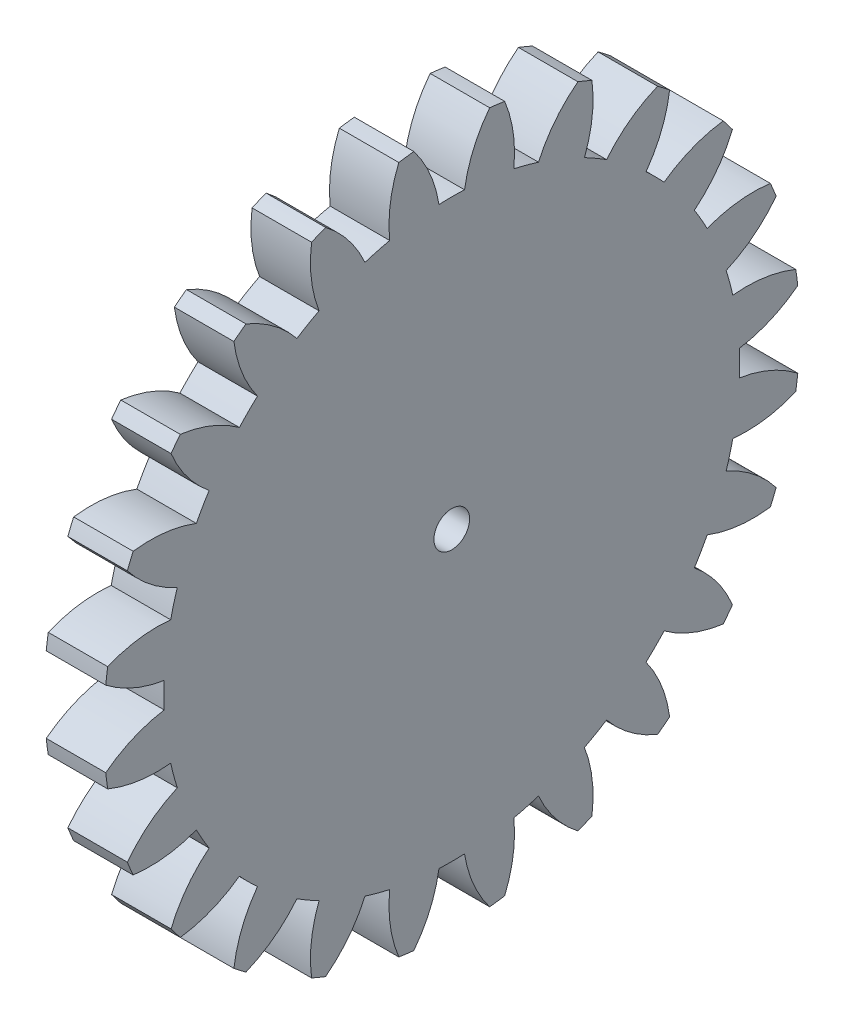
SolidWorks part; units mm, degrees
ref_plane "Plane1" through (0, 0, 0) normal (0, 0, 1) x (1, 0, 0)
ref_plane "Plane2" through (0, 0, 0) normal (0, 1, 0) x (1, 0, 0)
ref_plane "Plane3" through (0, 0, 0) normal (1, 0, 0) x (0, 0, -1)
other "Configuration Table"
sketch "HoldingSke" plane through (0, 0, 0) normal (0, 1, 0) x (1, 0, 0)
  line L0 (0, 0) -> (0.406, -0.1808)
  line L1 (-15, 0) -> (100, 0) construction
  line L2 (0, 0) -> (-2.1039, 2.3779)
  line L3 (0, 0) -> (-11.863, 4.5341)
  line L4 (0, 0) -> (7.8894, 3.5126)
  line L5 (0, 0) -> (-46.8476, -17.4728)
  line L6 (0, 0) -> (-4.1448, -2.7965)
  line L7 (-2.1039, 2.3779) -> (8.6586, 51.2059)
  line L8 (-76.2, 54.61) -> (-75.7, 54.61)
  line L9 (-71.009, 38.7566) -> (-53.1078, 45.2721)
  line L10 (-76.2, 71.12) -> (104.1128, 71.12)
  line L11 (0, 0) -> (-5, 0)
  line L12 (-76.2, 101.6) -> (-76.123, 101.6)
  line L13 (24.9733, 27.94) -> (52.9518, 28.4284)
  line L14 (24.9733, 27.94) -> (24.9743, 27.94)
  line L15 (24.9733, 27.94) -> (100.4006, 29.5858)
  line L16 (-63.627, -2.25) -> (-12.827, -2.25)
  circle A0 centre (0, 0) radius 1.5
  circle A1 centre (0, 0) radius 24.1865
  circle A2 centre (0, 0) radius 37.5
  circle A3 centre (0, 0) radius 1.5
  dimension "MHD" = 48.373
  dimension "Hub_dia" = 75
  dimension "Bore" = 3
  dimension "MBD" = 3
  dimension "Num_teeth" = 24
  dimension "Pitch" = 0.4444
  dimension "Overall_len" = 50
  dimension "Show_teeth" = 24
  dimension "Thickness" = 5
  dimension "OAL" = 50.0001
  dimension "T_dim" = 0.5
  dimension "Ap" = 20
  dimension "H" = 19.05
  dimension "Pitch_radius" = 180.3128
  dimension "Width" = 5
  dimension "Backlash" = 0.077
  dimension "Addendum_fac" = 1
  dimension "Dedendum_fac" = 1.25
  dimension "Clearance_fac" = 0.25
  dimension "Dedendum_add" = 0.001
  dimension "Module" = 2.25
sketch "BasProSke" plane through (0, 0, 0) normal (0, 1, 0) x (1, 0, 0)
  line L0 (-10, 0) -> (60, 0) construction
  line L1 (0, 0) -> (0, 29.25)
  line L2 (0, 0) -> (5, 0)
  line L3 (5, 0) -> (5, 29.25)
  line L4 (5, 29.25) -> (0, 29.25)
  dimension "Thickness" = 5
  dimension "Diameter" = 58.5
revolve "Base-Revolve" add sketch "BasProSke" angle 360 about L0
sketch "TooCutSke" plane through (0, 0, 0) normal (1, 0, 0) x (0, 0, -1)
  line L1 (0, 0) -> (0, 107) construction
  line L2 (0, 0) -> (-1.9006, 26.933) construction
  line L3 (0, 0) -> (-7.0355, 53.4402) construction
  line L4 (-1.9006, 26.933) -> (-3.5178, 26.7201) construction
  arc A0 (1.0746, 24.1626) -> (-1.0746, 24.1626) centre (0, 0) ccw
  arc A1 (3.2031, 29.0996) -> (-3.2031, 29.0996) centre (0, 0) ccw
  circle A2 centre (0, 0) radius 27 construction
  circle A3 centre (0, 0) radius 25.3717 construction
  arc A4 (-1.0746, 24.1626) -> (-3.2031, 29.0996) centre (-11.7443, 22.4899) ccw
  arc A5 (3.2031, 29.0996) -> (1.0746, 24.1626) centre (11.7443, 22.4899) ccw
  dimension "Root_dia" = 48.373
  dimension "Overcut_dia" = 58.5508
  dimension "Pitch_dia" = 54
  dimension "Base_dia" = 50.7434
  dimension "Flank_rad" = 10.8
  dimension "Half_ang" = 7.5
  dimension "Half_CT" = 1.6311
extrude "ToothCut" cut sketch "TooCutSke" along normal through all
fillet "Breaks" [suppressed] radius 0.045
fillet "RootFillets" [suppressed] radius 0.5635
pattern_circular "TeethCuts" count 24 every 15 about axis through (-10, 0, 0) along (1, 0, 0) of "ToothCut", "RootFillets", "Breaks"
sketch "HubNeaOneSke" plane through (0, 0, 0) normal (-1, 0, 0) x (0, 0, 1)
  circle A0 centre (0, 0) radius 24.1865
  dimension "Diameter" = 48.373
extrude "HubNearOne" [suppressed] add sketch "HubNeaOneSke" along normal blind 45.0001
sketch "HubNeaBotSke" plane through (0, 0, 0) normal (-1, 0, 0) x (0, 0, 1)
  circle A0 centre (0, 0) radius 24.1865
  dimension "Diameter" = 48.373
extrude "HubNearBoth" [suppressed] add sketch "HubNeaBotSke" along normal blind 22.5
ref_plane "FarPln" through (5, 0, 0) normal (1, 0, 0) x (0, 0, -1)
sketch "HubFarSke" plane through (5, 0, 0) normal (1, 0, 0) x (0, 0, -1)
  circle A0 centre (0, 0) radius 24.1865
  dimension "Diameter" = 48.373
extrude "HubFar" [suppressed] add sketch "HubFarSke" along normal blind 22.5
sketch "BorSke" plane through (0, 0, 0) normal (1, 0, 0) x (0, 0, -1)
  circle A0 centre (0, 0) radius 1.5
  dimension "Diameter" = 3
extrude "Bore" cut sketch "BorSke" along normal mid plane 100.0001
sketch "KeySke" plane through (0, 0, 0) normal (1, 0, 0) x (0, 0, -1)
  line L0 (-0.6, 0) -> (-0.6, 2)
  line L1 (-0.6, 2) -> (0.6, 2)
  line L2 (0.6, 2) -> (0.6, 0)
  line L3 (0, 0) -> (0, 34) construction
  line L4 (-0.6, 0) -> (0.6, 0)
  dimension "Offset" = 2
  dimension "Width" = 1.2
extrude "Keyway" [suppressed] cut sketch "KeySke" along normal mid plane 100.0001
pattern_circular "Keyway2" [suppressed] count 2 every 90 about axis through (-10, 0, 0) along (1, 0, 0)
equation "' \"Module@HoldingSke\" = 6.35"
equation "' \"Num_teeth@HoldingSke\" = 12"
equation "' \"Ap@HoldingSke\" =  20"
equation "' \"Ap@HoldingSke\" = 20"
equation "' \"Width@HoldingSke\" = 0.5 * 25.4"
equation "' \"Hub_dia@HoldingSke\"= 1 * 25.4"
equation "' \"Hub_dia@HoldingSke\" = 1 * 25.4"
equation "' \"Overall_len@HoldingSke\" = 1.0 * 25.4"
equation "' \"Bore@HoldingSke\" = 0.75 * 25.4"
equation "' \"T_dim@HoldingSke\" = 0.1 * 25.4"
equation "' \"Width@KeySke\" = 0.25 * 25.4"
equation "' \"Show_teeth@HoldingSke\" = 13"
equation "' \"Backlash@HoldingSke\" = 0.009 * 25.4"
equation "' \"Addendum_fac@HoldingSke\" = 1.0"
equation "' \"Dedendum_fac@HoldingSke\" = 1.25"
equation "' \"Dedendum_add@HoldingSke\" = 0.00005 * 25.4"
equation "' \"Clearance_fac@HoldingSke\" = 0.25"
equation "\"Pitch@HoldingSke\" = 1 / \"Module@HoldingSke\""
equation "\"Overcut_dia@TooCutSke\" = (\"Num_teeth@HoldingSke\" + 2 * \"Addendum_fac@HoldingSke\") / \"Pitch@HoldingSke\" + 0.002 * 25.4"
equation "\"Pitch_dia@TooCutSke\" = \"Num_teeth@HoldingSke\" / \"Pitch@HoldingSke\""
equation "\"Base_dia@TooCutSke\" = \"Num_teeth@HoldingSke\" / \"Pitch@HoldingSke\" * cos((\"Ap@HoldingSke\"  * 3.14159265 / 180))"
equation "\"Root_dia@TooCutSke\" = (\"Num_teeth@HoldingSke\" + 2) / \"Pitch@HoldingSke\" - 2 * (\"Addendum_fac@HoldingSke\" + \"Dedendum_fac@HoldingSke\") / \"Pitch@HoldingSke\" - \"Dedendum_add@HoldingSke\" * 2"
equation "\"Half_ang@TooCutSke\" = 180 / \"Num_teeth@HoldingSke\""
equation "\"Half_CT@TooCutSke\" = \"Num_teeth@HoldingSke\" / \"Pitch@HoldingSke\" * sin((3.14159265 / 2 / \"Num_teeth@HoldingSke\")) / 2 - 7 * \"Backlash@HoldingSke\" / 4"
equation "\"Flank_rad@TooCutSke\" = \"Num_teeth@HoldingSke\" / \"Pitch@HoldingSke\" / 5"
equation "\"Radius@RootFillets\" = \"Clearance_fac@HoldingSke\" / \"Pitch@HoldingSke\" + \"Dedendum_add@HoldingSke\""
equation "\"Break_rad@Breaks\" = 0.02 / \"Pitch@HoldingSke\""
equation "\"Thickness@HoldingSke\" = \"Width@HoldingSke\""
equation "\"OAL@HoldingSke\" = \"Thickness@HoldingSke\""
equation "\"MHD@HoldingSke\" = (\"Num_teeth@HoldingSke\" + 2) / \"Pitch@HoldingSke\" - 2 * (\"Addendum_fac@HoldingSke\" + \"Dedendum_fac@HoldingSke\")  / \"Pitch@HoldingSke\" - \"Dedendum_add@HoldingSke\" * 2"
equation "\"MBD@HoldingSke\" = (\"Num_teeth@HoldingSke\" + 2) / \"Pitch@HoldingSke\" - 2 * (\"Addendum_fac@HoldingSke\" + \"Dedendum_fac@HoldingSke\")  / \"Pitch@HoldingSke\" - \"Dedendum_add@HoldingSke\" * 2 - 0.002 * 25.4"
equation "\"MHD@HoldingSke\" = ((sgn( \"MHD@HoldingSke\" - \"Hub_dia@HoldingSke\" )-1)*( \"MHD@HoldingSke\" - \"Hub_dia@HoldingSke\" ))/-2+ \"Hub_dia@HoldingSke\""
equation "\"MBD@HoldingSke\" = ((sgn( \"MBD@HoldingSke\" - \"Bore@HoldingSke\" )-1)*( \"MBD@HoldingSke\" - \"Bore@HoldingSke\" ))/-2+ \"Bore@HoldingSke\""
equation "\"OAL@HoldingSke\" = ((sgn( \"OAL@HoldingSke\" - \"Overall_len@HoldingSke\" )+1)*( \"OAL@HoldingSke\" - \"Overall_len@HoldingSke\" ))/2 + \"Overall_len@HoldingSke\" + 0.000002 * 25.4"
equation "\"Num_teeth@TeethCuts\" = int( \"Show_teeth@HoldingSke\" ) + 1"
equation "\"Num_teeth@TeethCuts\" = ((sgn( \"Num_teeth@TeethCuts\" - \"Num_teeth@HoldingSke\" )-1)*( \"Num_teeth@TeethCuts\" - \"Num_teeth@HoldingSke\" ))/-2+ \"Num_teeth@HoldingSke\""
equation "\"Num_teeth@TeethCuts\" = ((sgn( \"Num_teeth@TeethCuts\" - 2.0)+1)*( \"Num_teeth@TeethCuts\" - 2.0))/2 +2.0"
equation "\"Angle@TeethCuts\" = 360.0 / \"Num_teeth@HoldingSke\""
equation "\"Diameter@BasProSke\" = (\"Num_teeth@HoldingSke\" + 2 * \"Addendum_fac@HoldingSke\") / \"Pitch@HoldingSke\""
equation "\"Thickness@BasProSke\"  = \"Thickness@HoldingSke\""
equation "' \"Fillet_rad@BasProSke\" =  \"Thickness@HoldingSke\" * 0.05"
equation "' \"Fillet_rad@BasProSke\" = \"Thickness@HoldingSke\" * 0.05"
equation "\"MHD@HoldingSke\" = ((sgn( \"MHD@HoldingSke\" - \"Root_dia@TooCutSke\" )-1)*( \"MHD@HoldingSke\" - \"Root_dia@TooCutSke\" ))/-2+ \"Root_dia@TooCutSke\""
equation "\"Diameter@HubNeaOneSke\" = \"MHD@HoldingSke\""
equation "\"Length@HubNearOne\" = \"OAL@HoldingSke\" - \"Thickness@BasProSke\""
equation "\"Diameter@HubNeaBotSke\" = \"MHD@HoldingSke\""
equation "\"Length@HubNearBoth\" = ( \"OAL@HoldingSke\" - \"Thickness@BasProSke\" ) / 2.0"
equation "\"Thickness@FarPln\" = \"Thickness@BasProSke\""
equation "\"Diameter@HubFarSke\" = \"MHD@HoldingSke\""
equation "\"Length@HubFar\" = ( \"OAL@HoldingSke\" - \"Thickness@BasProSke\" ) / 2.0"
equation "\"Diameter@BorSke\" = \"MBD@HoldingSke\""
equation "\"D1@Bore\" = \"OAL@HoldingSke\" * 2.0"
equation "\"D1@Keyway\" = \"OAL@HoldingSke\" * 2.0"
equation "\"Offset@KeySke\" = \"T_dim@HoldingSke\" + \"MBD@HoldingSke\" / 2.0"
